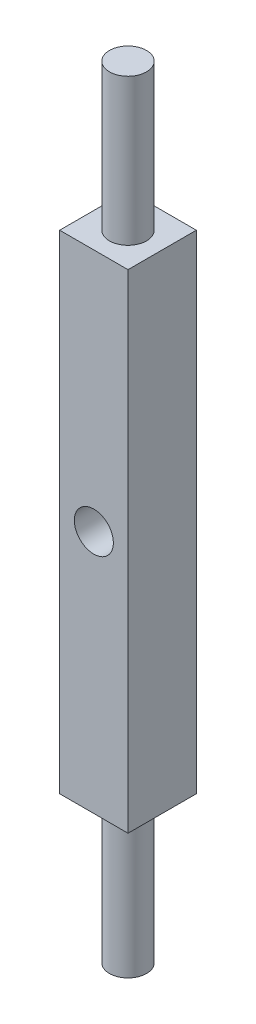
SolidWorks part; units mm, degrees
ref_plane "Front Plane" through (0, 0, 0) normal (0, 0, 1) x (1, 0, 0)
ref_plane "Top Plane" through (0, 0, 0) normal (0, 1, 0) x (1, 0, 0)
ref_plane "Right Plane" through (0, 0, 0) normal (1, 0, 0) x (0, 0, -1)
sketch "Sketch2" plane through (0, 0, 0) normal (0, 1, 0) x (1, 0, 0)
  line L1 (-3.5, 3.5) -> (3.5, 3.5)
  line L2 (-3.5, 3.5) -> (-3.5, -3.5)
  line L3 (-3.5, -3.5) -> (3.5, -3.5)
  line L4 (3.5, 3.5) -> (3.5, -3.5)
  line L5 (-3.5, 3.5) -> (3.5, -3.5) construction
  line L6 (-3.5, -3.5) -> (3.5, 3.5) construction
  point P0 (0, 0)
  dimension "D1" = 7
  dimension "D2" = 7
extrude "Boss-Extrude1" add sketch "Sketch2" along normal blind 50
sketch "Sketch3" plane through (0, 0, 0) normal (0, -1, 0) x (1, 0, 0)
  circle A0 centre (0, 0) radius 1.9
  dimension "D1" = 3.8
extrude "Boss-Extrude3" add sketch "Sketch3" along normal blind 15 and the other way blind 65
sketch "Sketch4" plane through (0, 0, 3.5) normal (0, 0, 1) x (1, 0, 0)
  line L0 (0, -950) -> (0, 49050) construction
  line L1 (-3.5, 50) -> (3.5, 50) construction
  line L2 (-997.323, 25.0104) -> (49002.677, 25.0104) construction
  circle A0 centre (0, 25.0104) radius 2
  point P5 (0, 50)
  dimension "D1" = 4
extrude "Cut-Extrude1" cut sketch "Sketch4" against normal blind 10
